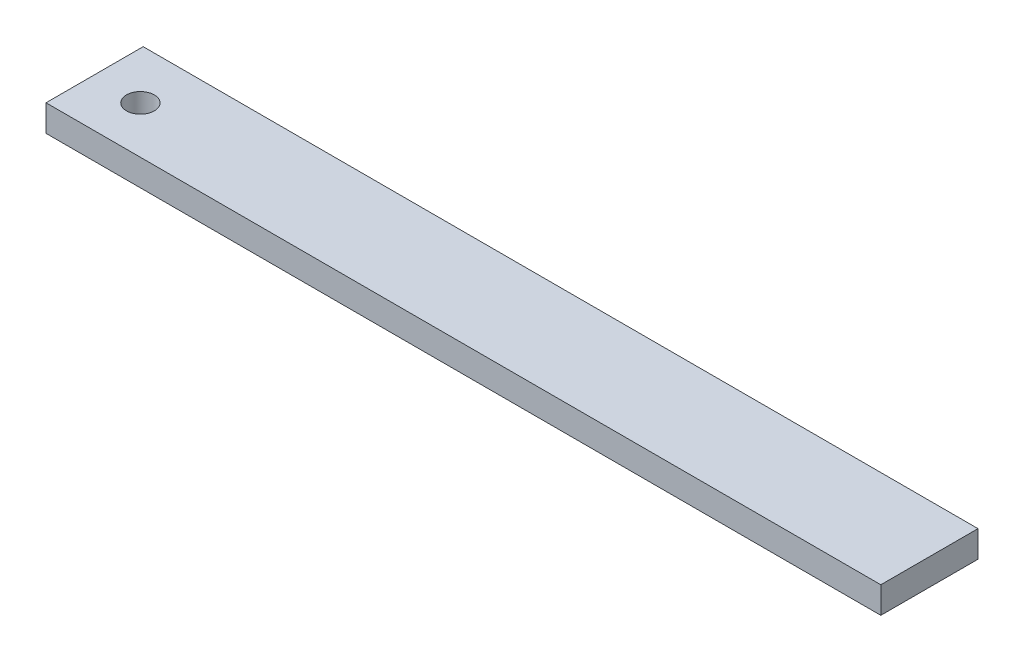
SolidWorks part; units mm, degrees
ref_plane "Front Plane" through (0, 0, 0) normal (0, 0, 1) x (1, 0, 0)
ref_plane "Top Plane" through (0, 0, 0) normal (0, 1, 0) x (1, 0, 0)
ref_plane "Right Plane" through (0, 0, 0) normal (1, 0, 0) x (0, 0, -1)
sketch "Sketch1" plane through (0, 0, 0) normal (0, 1, 0) x (1, 0, 0)
  line L0 (-300, 16.925) -> (-283, 16.925) construction
  line L1 (0, 0) -> (-300, 0)
  line L2 (0, 0) -> (0, 34.925)
  line L3 (0, 34.925) -> (-300, 34.925)
  line L4 (-300, 0) -> (-300, 34.925)
  circle A0 centre (-283, 16.925) radius 5
  dimension "D3" = 17
  dimension "D1" = 300
  dimension "D2" = 34.925
  dimension "D4" = 18
  dimension "D5" = 18
extrude "Boss-Extrude1" add sketch "Sketch1" along normal blind 9.525
